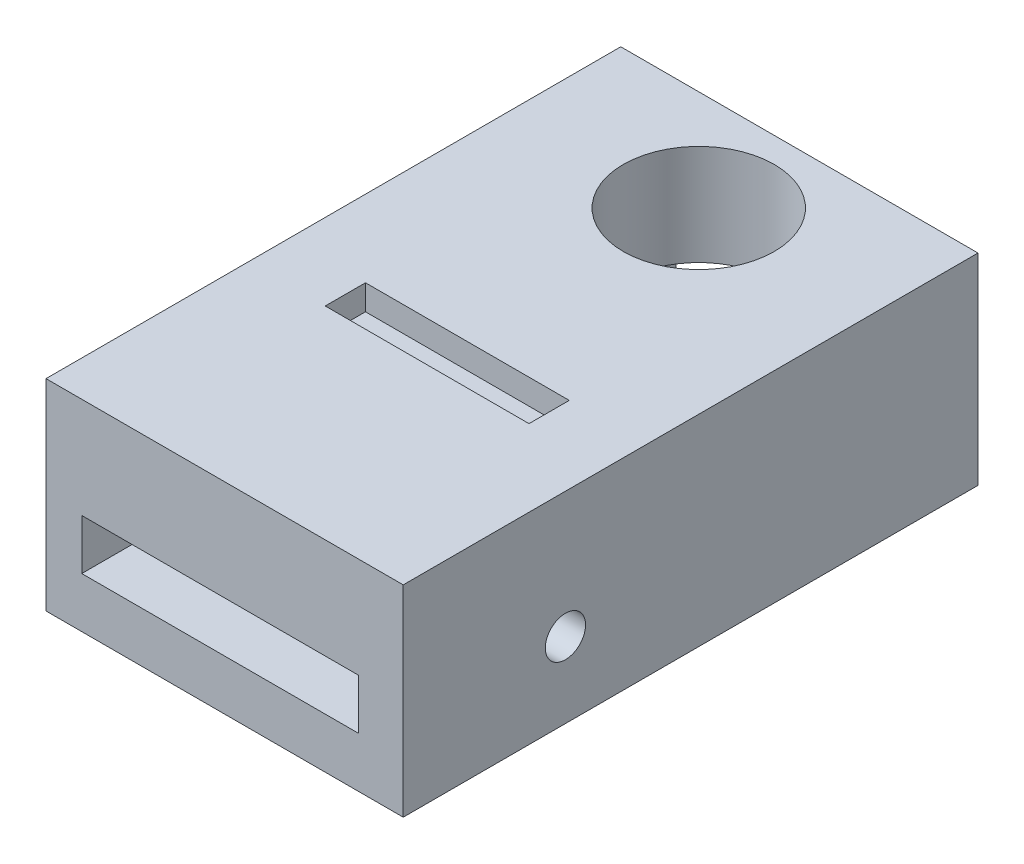
SolidWorks part; units mm, degrees
material "Balsa"
ref_plane "Plan de face" through (0, 0, 0) normal (0, 0, 1) x (1, 0, 0)
ref_plane "Plan de dessus" through (0, 0, 0) normal (0, 1, 0) x (1, 0, 0)
ref_plane "Plan de droite" through (0, 0, 0) normal (1, 0, 0) x (0, 0, -1)
sketch "Sketch1" plane through (0, 0, 0) normal (0, 1, 0) x (1, 0, 0)
  line L1 (-35.5, -32.12) -> (35.5, -32.12)
  line L2 (-35.5, -32.12) -> (-35.5, 32.12)
  line L3 (-35.5, 32.12) -> (35.5, 32.12)
  line L4 (35.5, -32.12) -> (35.5, 32.12)
  line L5 (-35.5, -32.12) -> (35.5, 32.12) construction
  line L6 (-35.5, 32.12) -> (35.5, -32.12) construction
  point P0 (0, 0)
  dimension "D1" = 71
  dimension "D2" = 64.24
extrude "Boss-Extrude1" add sketch "Sketch1" along normal blind 40
sketch "Sketch2" plane through (-35.5, 0, 0) normal (-1, 0, 0) x (0, 0, 1)
  line L0 (-32.12, 40) -> (-32.12, 0) construction
  line L1 (-32.12, 0) -> (32.12, 0) construction
  circle A0 centre (-0.12, 15) radius 4
  dimension "D1" = 8
  dimension "D2" = 32
  dimension "D3" = 15
extrude "Cut-Extrude2" cut sketch "Sketch2" against normal blind 10
sketch "Sketch5" plane through (0, 0, -32.12) normal (0, 0, -1) x (-1, 0, 0)
  line L1 (-35.5, 40) -> (35.5, 40)
  line L2 (-35.5, 40) -> (-35.5, 0)
  line L3 (-35.5, 0) -> (35.5, 0)
  line L4 (35.5, 40) -> (35.5, 0)
extrude "Boss-Extrude2" add sketch "Sketch5" along normal blind 50
sketch "Sketch6" plane through (0, 40, 0) normal (0, 1, 0) x (1, 0, 0)
  line L0 (-35.5, 82.12) -> (35.5, 82.12) construction
  circle A0 centre (0, 62.12) radius 15
  dimension "D1" = 30
  dimension "D2" = 20
extrude "Cut-Extrude3" cut sketch "Sketch6" against normal through all
sketch "Sketch8" plane through (0, 40, 0) normal (0, 1, 0) x (1, 0, 0)
  line L1 (-20.25, 16.13) -> (20.25, 16.13)
  line L2 (-20.25, 16.13) -> (-20.25, 8.13)
  line L3 (-20.25, 8.13) -> (20.25, 8.13)
  line L4 (20.25, 16.13) -> (20.25, 8.13)
  line L7 (-35.5, -32.12) -> (35.5, -32.12) construction
  dimension "D1" = 40.25
  dimension "D2" = 8
extrude "Cut-Extrude5" cut sketch "Sketch8" against normal blind 5
sketch "Sketch9" plane through (35.5, 0, 0) normal (1, 0, 0) x (0, 0, -1)
  line L1 (-32.12, 0) -> (82.12, 0) construction
  line L2 (-32.12, 40) -> (-32.12, 0) construction
  circle A0 centre (0.12, 15) radius 4
  dimension "D1" = 8
  dimension "D2" = 15
  dimension "D3" = 32.24
extrude "Cut-Extrude6" cut sketch "Sketch9" against normal blind 10
sketch "Sketch10" plane through (0, 0, 32.12) normal (0, 0, 1) x (1, 0, 0)
  line L1 (-28.3908, 10) -> (26.6092, 10)
  line L2 (-28.3908, 10) -> (-28.3908, 20)
  line L3 (-28.3908, 20) -> (26.6092, 20)
  line L4 (26.6092, 10) -> (26.6092, 20)
  line L5 (-28.3908, 10) -> (26.6092, 20) construction
  line L6 (-28.3908, 20) -> (26.6092, 10) construction
  line L7 (-35.5, 40) -> (35.5, 40) construction
  point P0 (-0.8908, 15)
  dimension "D1" = 55
  dimension "D2" = 10
  dimension "D3" = 20
extrude "Cut-Extrude7" cut sketch "Sketch10" against normal through all
sketch "Sketch11" plane through (0, 0, 0) normal (0, -1, 0) x (-1, 0, 0)
  line L0 (-35.5, 82.12) -> (35.5, 82.12) construction
  line L1 (-26.61, 82.12) -> (24.5, 82.12)
  line L2 (-26.61, 82.12) -> (-26.61, 44.12)
  line L3 (-26.61, 44.12) -> (24.5, 44.12)
  line L4 (24.5, 82.12) -> (24.5, 44.12)
  line L5 (35.5, 82.12) -> (35.5, -32.12) construction
  line L6 (-35.5, -32.12) -> (-35.5, 82.12) construction
  dimension "D1" = 38
  dimension "D2" = 11
  dimension "D3" = 8.89
extrude "Cut-Extrude8" cut sketch "Sketch11" against normal blind 10
